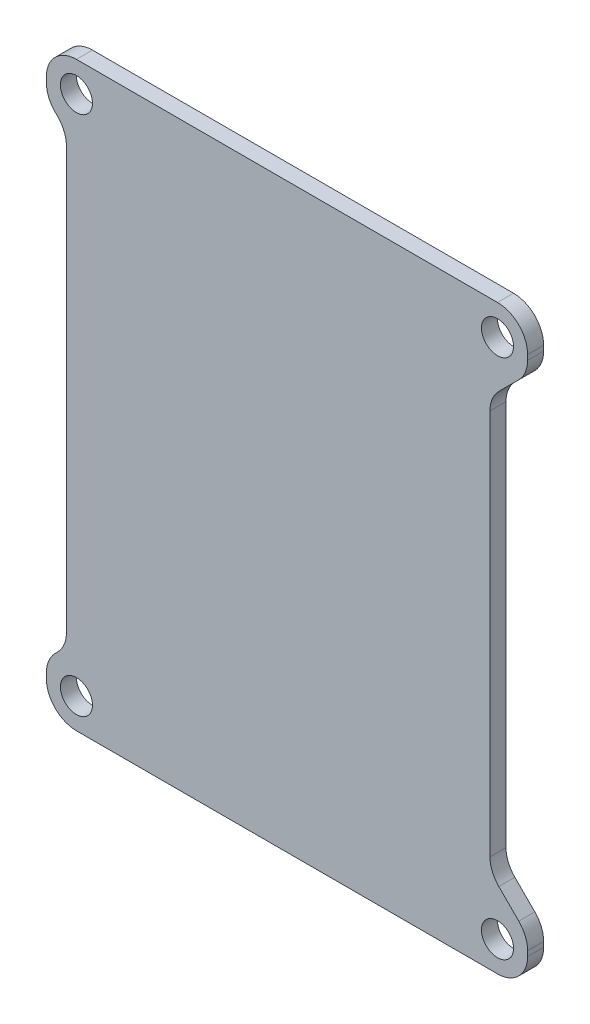
SolidWorks part; units mm, degrees
ref_plane "Front Plane" through (0, 0, 0) normal (0, 0, 1) x (1, 0, 0)
ref_plane "Top Plane" through (0, 0, 0) normal (0, 1, 0) x (1, 0, 0)
ref_plane "Right Plane" through (0, 0, 0) normal (1, 0, 0) x (0, 0, -1)
sketch "Sketch1" plane through (0, 0, 0) normal (0, 0, 1) x (1, 0, 0)
  line L0 (23.1213, 23.3787) -> (21.1287, 21.386)
  line L1 (-21, 29) -> (21, 29)
  line L2 (-24, 26) -> (-24, 25.5)
  line L3 (-21, -29) -> (21, -29)
  line L4 (24, 26) -> (24, 25.5)
  line L5 (-21, 26) -> (21, 26) construction
  line L6 (-21, 26) -> (-21, -26) construction
  line L7 (-21, -26) -> (21, -26) construction
  line L8 (21, 26) -> (21, -26) construction
  line L9 (20.25, 19.2647) -> (20.25, -19.2647)
  line L10 (21.1287, -21.386) -> (23.1213, -23.3787)
  line L11 (24, -25.5) -> (24, -26)
  line L12 (-23.1213, 23.3787) -> (-22.8787, 23.136)
  line L13 (-22, 21.0147) -> (-22, -21.0147)
  line L14 (-22.8787, -23.136) -> (-23.1213, -23.3787)
  line L15 (-24, -25.5) -> (-24, -26)
  circle A0 centre (-21, 26) radius 1.6
  circle A1 centre (21, 26) radius 1.6
  circle A2 centre (21, -26) radius 1.6
  circle A3 centre (-21, -26) radius 1.6
  arc A4 (-24, 26) -> (-21, 29) centre (-21, 26) cw
  arc A5 (-24, -26) -> (-21, -29) centre (-21, -26) ccw
  arc A6 (21, -29) -> (24, -26) centre (21, -26) ccw
  arc A7 (21, 29) -> (24, 26) centre (21, 26) cw
  arc A8 (24, -25.5) -> (23.1213, -23.3787) centre (21, -25.5) ccw
  arc A9 (20.25, -19.2647) -> (21.1287, -21.386) centre (23.25, -19.2647) ccw
  arc A10 (21.1287, 21.386) -> (20.25, 19.2647) centre (23.25, 19.2647) ccw
  arc A11 (24, 25.5) -> (23.1213, 23.3787) centre (21, 25.5) cw
  arc A12 (-23.1213, -23.3787) -> (-24, -25.5) centre (-21, -25.5) ccw
  arc A13 (-22.8787, -23.136) -> (-22, -21.0147) centre (-25, -21.0147) ccw
  arc A14 (-22.8787, 23.136) -> (-22, 21.0147) centre (-25, 21.0147) cw
  arc A15 (-23.1213, 23.3787) -> (-24, 25.5) centre (-21, 25.5) cw
  point P15 (-24, 29)
  point P18 (-24, -29)
  point P23 (24, 29)
  point P32 (24, -18.2812)
  point P35 (21.1287, -20.2782)
  point P38 (21, 21.5)
  point P41 (24, 24.2574)
  point P45 (-24, -23.7574)
  point P53 (0, 0)
  point P54 (0, 0)
  point P55 (0, 0)
  point P56 (0, 0)
  point P57 (0, 0)
  point P58 (0, 0)
  point P59 (0, 0)
  point P60 (0, 0)
  point P61 (0, 0)
  point P62 (0, 0)
  point P63 (-23.1213, 14.4995)
  point P64 (0, 0)
  point P65 (-21, 19.5887)
  point P66 (0, 0)
  point P67 (0, 0)
  point P68 (-21, 21.5)
  point P69 (0, 0)
  point P70 (0, 0)
  point P71 (0, 0)
  point P72 (0, 0)
  point P73 (0, 0)
  point P74 (-23.8787, 24.136)
  dimension "D9" = 3.2
  dimension "D10" = 3
  dimension "D15" = 3
  dimension "D18" = 3
  dimension "D1" = 48
  dimension "D2" = 58
  dimension "D3" = 29
  dimension "D4" = 24
  dimension "D5" = 42
  dimension "D6" = 52
  dimension "D7" = 21
  dimension "D8" = 26
  dimension "D13" = 45
  dimension "D14" = 45
  dimension "D16" = 1.5
  dimension "D17" = 45
  dimension "D11" = 0.5
  dimension "D12" = 0.5
  dimension "D19" = 1
extrude "Boss-Extrude1" add sketch "Sketch1" along normal blind 1.6
equation "\"pcb_thickness\"= 1.6mm"
equation "\"pcb_width\" = 48mm"
equation "\"pcb_height\" = 58mm"
equation "\"D1@Sketch1\"=\"pcb_width\""
equation "\"D2@Sketch1\"=\"pcb_height\""
equation "\"D3@Sketch1\"=\"pcb_height\"/2"
equation "\"D4@Sketch1\"=\"pcb_width\"/2"
equation "\"D1@Boss-Extrude1\"=\"pcb_thickness\""
equation "\"D7@Sketch1\"=42/2"
equation "\"D8@Sketch1\"=52/2"
